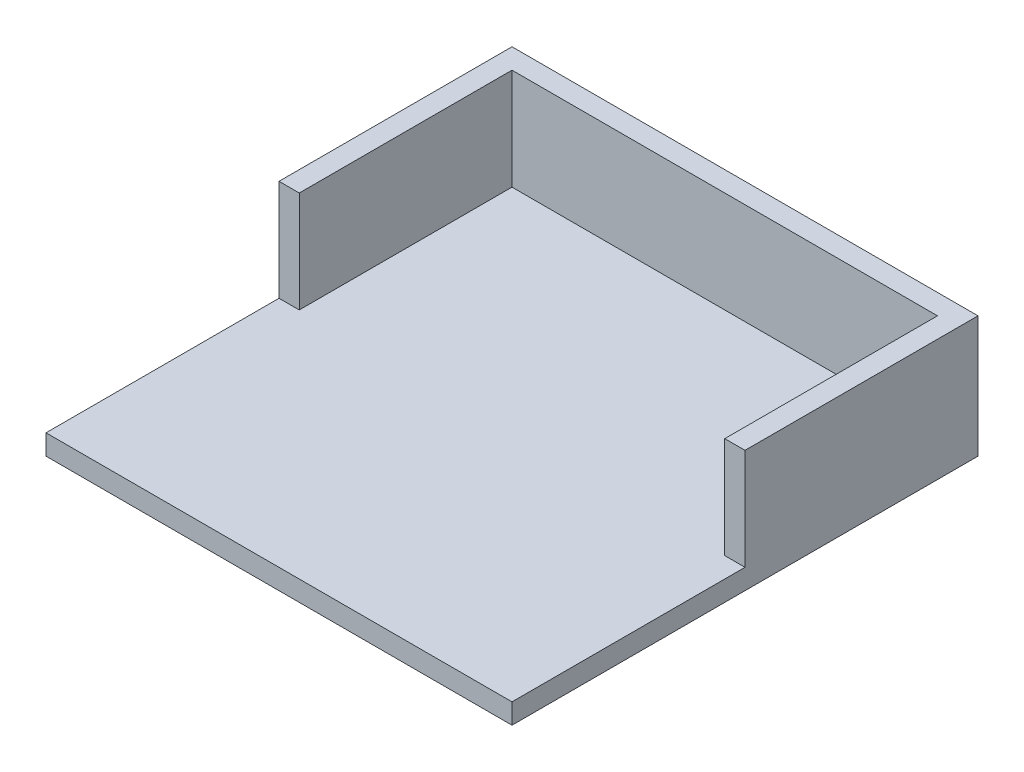
SolidWorks part; units mm, degrees
ref_plane "Front Plane" through (0, 0, 0) normal (0, 0, 1) x (1, 0, 0)
ref_plane "Top Plane" through (0, 0, 0) normal (0, 1, 0) x (1, 0, 0)
ref_plane "Right Plane" through (0, 0, 0) normal (1, 0, 0) x (0, 0, -1)
sketch "Sketch1" plane through (0, 0, 0) normal (0, 1, 0) x (1, 0, 0)
  line L1 (0, 0) -> (46, 0)
  line L2 (0, 0) -> (0, 46)
  line L3 (0, 46) -> (46, 46)
  line L4 (46, 0) -> (46, 46)
  dimension "D1" = 46
  dimension "D2" = 46
extrude "Boss-Extrude1" add sketch "Sketch1" along normal blind 2
sketch "Sketch2" plane through (0, 2, 0) normal (0, 1, 0) x (1, 0, 0)
  line L5 (0, 46) -> (46, 46)
  line L6 (0, 46) -> (0, 0)
  line L7 (0, 0) -> (46, 0)
  line L8 (2, 44) -> (2, 2)
  line L9 (2, 2) -> (44, 2)
  line L10 (44, 2) -> (44, 44)
  line L11 (44, 44) -> (2, 44)
  line L12 (2, 44) -> (2, 2)
  line L13 (2, 2) -> (44, 2)
  line L14 (44, 2) -> (44, 44)
  line L15 (44, 44) -> (2, 44)
  line L16 (46, 46) -> (46, 0)
  dimension "D1" = 2
extrude "Boss-Extrude2" add sketch "Sketch2" along normal blind 10
sketch "Sketch3" plane through (0, 12, 0) normal (0, 1, 0) x (1, 0, 0)
  line L0 (46, 0) -> (46, 46) construction
  line L1 (0, 0) -> (46, 0)
  line L2 (0, 0) -> (0, 23)
  line L3 (0, 23) -> (46, 23)
  line L4 (46, 0) -> (46, 23)
extrude "Cut-Extrude1" cut sketch "Sketch3" against normal blind 10
